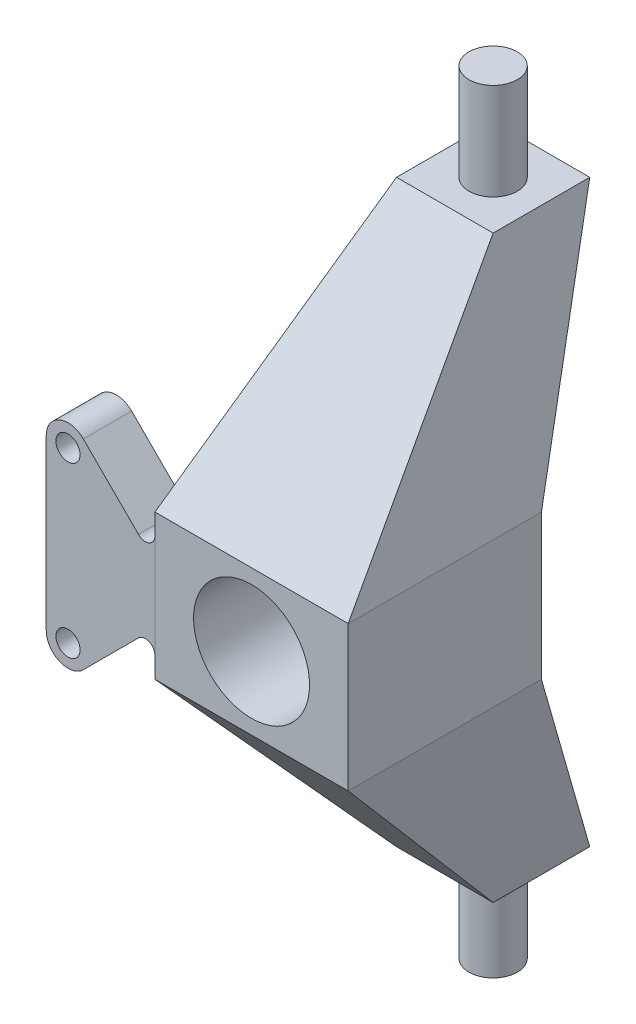
SolidWorks part; units mm, degrees
material "Cast Alloy Steel"
ref_plane "Front Plane" through (0, 0, 0) normal (0, 0, 1) x (1, 0, 0)
ref_plane "Top Plane" through (0, 0, 0) normal (0, 1, 0) x (1, 0, 0)
ref_plane "Right Plane" through (0, 0, 0) normal (1, 0, 0) x (0, 0, -1)
sketch "Sketch1" plane through (0, 0, 0) normal (1, 0, 0) x (0, 0, -1)
  line L0 (20, 0) -> (-20, 0)
  line L1 (-20, -15) -> (-20, 15)
  line L2 (-20, 15) -> (20, 60)
  line L3 (20, 60) -> (40, 60)
  line L4 (40, 60) -> (20, 15)
  line L5 (20, 15) -> (20, -15)
  line L6 (-59.1587, 0) -> (64.9977, 0) construction
  line L7 (40, -60) -> (20, -15)
  line L8 (20, -60) -> (40, -60)
  line L9 (-20, -15) -> (20, -60)
  point P0 (0, 0)
  dimension "D1" = 15
  dimension "D2" = 40
  dimension "D3" = 45
  dimension "D4" = 40
  dimension "D5" = 20
extrude "Boss-Extrude1" add sketch "Sketch1" along normal mid plane 40 contours L5 L4 L3 L2 L1 L0 | L1 L9 L8 L7 L5 L0
sketch "Sketch2" plane through (0, 0, 20) normal (0, 0, 1) x (1, 0, 0)
  circle A0 centre (0, 0) radius 12
  dimension "D1" = 24
extrude "Cut-Extrude1" cut sketch "Sketch2" against normal through all both and the other way through all
sketch "Sketch3" plane through (0, 0, 20) normal (0, 0, 1) x (1, 0, 0)
  line L0 (-23.4142, 9.2782) -> (-34.818, 20.682)
  line L1 (-20, -15) -> (-20, 15) construction
  line L2 (-42.5, 17.5) -> (-42.5, -17.5)
  line L3 (-34.818, -20.682) -> (-23.4142, -9.2782)
  line L4 (-20, -15) -> (-20, -10.6924)
  line L5 (-20, 10.6924) -> (-20, 15)
  arc A0 (-20, -10.6924) -> (-23.4142, -9.2782) centre (-22, -10.6924) ccw
  arc A1 (-20, 10.6924) -> (-23.4142, 9.2782) centre (-22, 10.6924) cw
  arc A2 (-34.818, -20.682) -> (-42.5, -17.5) centre (-38, -17.5) cw
  arc A3 (-42.5, 17.5) -> (-34.818, 20.682) centre (-38, 17.5) cw
  circle A4 centre (-38, 17.5) radius 2.5
  circle A5 centre (-38, -17.5) radius 2.5
  arc A6 (-42.5, -17.5) -> (-34.818, -20.682) centre (-38, -17.5) ccw
  circle A7 centre (-38, -17.5) radius 4.5 construction
  point P8 (-20, -5.864)
  point P11 (-20, 5.864)
  point P18 (-42.5, 0)
  line M8 (-20, 15) -> (-20, -15)
  dimension "D1" = 2
  dimension "D2" = 2
  dimension "D4" = 5
  dimension "D3" = 35
  dimension "D5" = 18
  dimension "D6" = 45
extrude "Boss-Extrude2" add sketch "Sketch3" against normal blind 10 separate body contours A3 L2 A2 L3 A0 A1 L0 A5 A4 M8
sketch "Sketch5" plane through (0, 60, 0) normal (0, 1, 0) x (1, 0, 0)
  line L0 (0, 30) -> (0, 40) construction
  line L1 (20, 40) -> (-20, 40) construction
  line L2 (0, 30) -> (20, 30) construction
  line L3 (20, 20) -> (20, 40) construction
  circle A0 centre (0, 30) radius 5
  dimension "D1" = 10
extrude "Boss-Extrude3" add sketch "Sketch5" along normal blind 20
mirror "Mirror1" about plane through (0, 0, 0) normal (0, 1, 0) of "Boss-Extrude3"
sketch "Sketch6" plane through (0, 0, 20) normal (0, 0, 1) x (1, 0, 0)
  line L0 (-20, 15) -> (-10, 60)
  line L1 (20, 60) -> (-20, 60) construction
  line L2 (20, 15) -> (10, 60)
  line L4 (-20, 15) -> (-20, -15)
  line L5 (-20, -15) -> (20, -15)
  line L6 (20, -15) -> (20, 15)
  line L7 (20, 15) -> (-20, 15)
  line L10 (20, -15) -> (20, 15)
  line L12 (-10, 60) -> (-20, 60)
  line L16 (-20, 60) -> (-20, 15)
  line L17 (-20, 15) -> (20, 15)
  line L18 (20, 15) -> (20, 60)
  line L19 (20, 60) -> (-20, 60)
  line L20 (-20, 60) -> (-20, 15)
  line L22 (20, 15) -> (20, 60)
  line L23 (20, 60) -> (10, 60)
  dimension "D2" = 10
  dimension "D1" = 0
  dimension "D3" = 0
extrude "Cut-Extrude2" cut sketch "Sketch6" against normal through all both and the other way through all contours L22 L23 L2 | L20 L0 L12
mirror "Mirror2" about plane through (0, 0, 0) normal (0, 1, 0) of "Cut-Extrude2"
equation "\"A\"= 40"
equation "\"B\"= 120"
equation "\"C\"= 20"
equation "\"D\"= \"B\" / 4"
equation "\"E\"= \"C\" / 2"
equation "\"D1@Sketch1\"=\"D\"/2"
equation "\"D2@Sketch1\"=\"A\""
equation "\"D5@Sketch1\"=\"C\""
equation "\"D1@Sketch5\"=\"E\""
equation "\"D1@Boss-Extrude3\"=\"C\""
